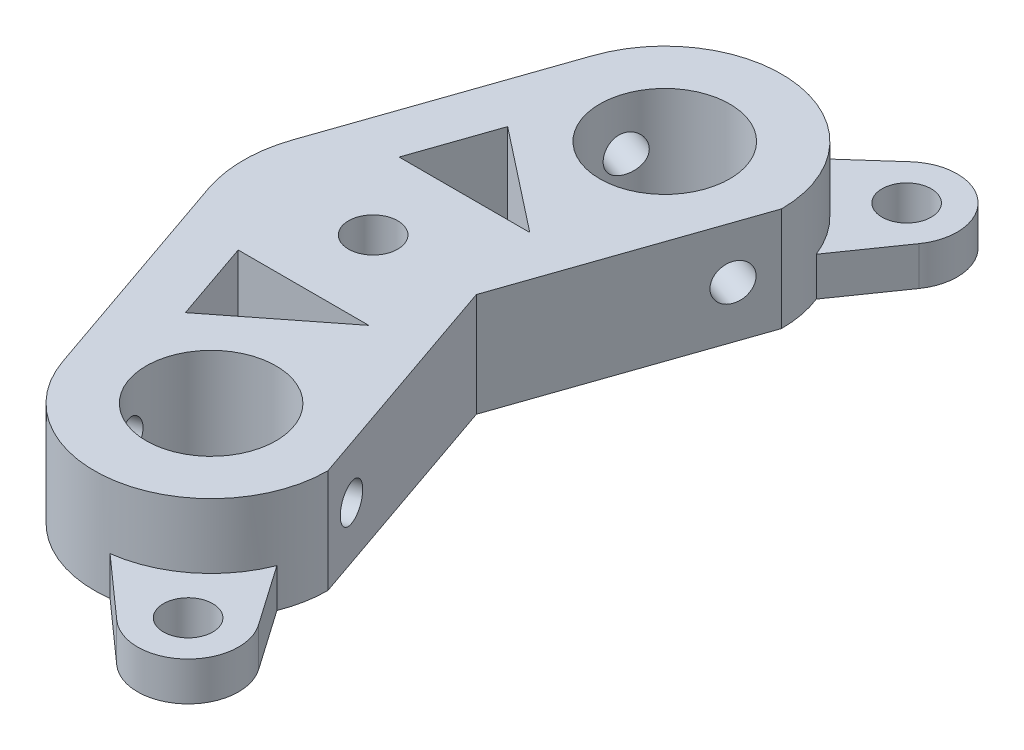
SolidWorks part; units mm, degrees
ref_plane "Front Plane" through (0, 0, 0) normal (0, 0, 1) x (1, 0, 0)
ref_plane "Top Plane" through (0, 0, 0) normal (0, 1, 0) x (1, 0, 0)
ref_plane "Right Plane" through (0, 0, 0) normal (1, 0, 0) x (0, 0, -1)
sketch "Sketch1" plane through (0, 0, 0) normal (0, 1, 0) x (1, 0, 0)
  line L0 (0, 0) -> (69.6737, 0) construction
  line L1 (5, -17.5) -> (5, 17.5) construction
  line L2 (-9.4516, 3.2662) -> (-3.5159, 20.4428)
  line L3 (-9.4516, -3.2662) -> (-3.5159, -20.4428)
  line L5 (7.9626, 0) -> (14.01, -17.5)
  line L6 (7.9626, 0) -> (14.01, 17.5)
  circle A0 centre (0, 0) radius 1.9
  arc A1 (-9.4516, 3.2662) -> (-9.4516, -3.2662) centre (0, 0) ccw
  circle A2 centre (5, 17.5) radius 5.01
  arc A3 (14.01, 17.5) -> (-3.5159, 20.4428) centre (5, 17.5) ccw
  circle A4 centre (5, -17.5) radius 5.01
  arc A5 (-3.5159, -20.4428) -> (14.01, -17.5) centre (5, -17.5) ccw
  point P8 (5, 0)
  point P28 (-10, 0)
  dimension "D1" = 3.8
  dimension "D2" = 10.02
  dimension "D3" = 4
  dimension "D5" = 10
  dimension "D4" = 35
  dimension "D7" = 15
extrude "Boss-Extrude1" add sketch "Sketch1" along normal blind 8
sketch "Sketch2" plane through (0, 0, 0) normal (0, 1, 0) x (1, 0, 0)
  line L3 (13.3811, 20.8072) -> (16.6424, 25.4881)
  line L4 (13.3811, 20.8072) -> (6.142, 26.4373)
  line L5 (6.142, 26.4373) -> (10.8485, 30.6297)
  arc A3 (16.6424, 25.4881) -> (10.8485, 30.6297) centre (13.4426, 27.7176) ccw
  circle A4 centre (13.4426, 27.7176) radius 1.9
  arc A5 (14.01, 17.5) -> (-3.5159, 20.4428) centre (5, 17.5) ccw construction
  point P0 (13.3811, 27.7176)
  dimension "D1" = 3.8
  dimension "D2" = 2
extrude "Boss-Extrude2" add sketch "Sketch2" along normal blind 3
sketch "Sketch3" plane through (7.1131, 0, 2.4581) normal (0.9452, 0, 0.3266) x (0.3266, 0, -0.9452)
  line L1 (18.1733, 0) -> (18.1733, 8) construction
  line L2 (2.6007, 0) -> (21.1161, 0) construction
  line L3 (2.6007, 8) -> (21.1161, 8) construction
  line L4 (18.1733, 8) -> (18.1733, 0) construction
  circle A0 centre (18.1733, 4) radius 1.4
  dimension "D1" = 2.8
extrude "Cut-Extrude1" cut sketch "Sketch3" against normal blind 22
mirror "Mirror1" about plane through (0, 0, 0) normal (0, 0, 1) of "Cut-Extrude1"
sketch "Sketch5" plane through (0, 0, 0) normal (0, 1, 0) x (1, 0, 0)
  line L0 (-2.0525, 12.4307) -> (-4.2028, 6.2081)
  line L1 (-4.2028, 6.2081) -> (5.8758, 6.2081)
  line L2 (5.8758, 6.2081) -> (-2.0525, 12.4307)
  line L3 (-9.4516, 3.2662) -> (-3.5159, 20.4428) construction
  line L4 (7.9626, 0) -> (14.01, 17.5) construction
  point P2 (6.6424, 6.2677)
  point P4 (-2.6423, 6.2677)
  point P7 (8.2517, 5.7725)
  point P8 (-1.8995, 12.3336)
  point P9 (5.652, 6.1439)
  point P12 (-2.0525, 12.4307)
  dimension "D1" = 4
  dimension "D2" = 4
extrude "Cut-Extrude3" cut sketch "Sketch5" along normal up to surface (8 mm away) up to face at (0, 8, 1.9)
mirror "Mirror3" about plane through (0, 0, 0) normal (0, 0, 1) of "Cut-Extrude1", "Mirror1", "Cut-Extrude3", "Boss-Extrude2"
